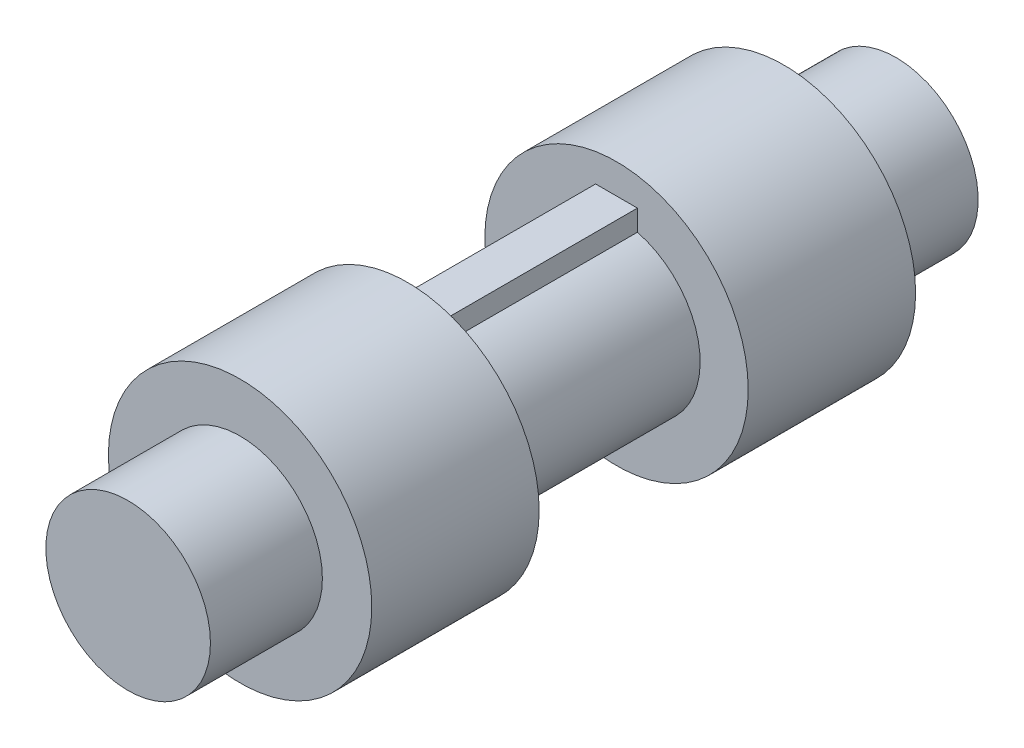
SolidWorks part; units mm, degrees
ref_plane "Front Plane" through (0, 0, 0) normal (0, 0, 1) x (1, 0, 0)
ref_plane "Top Plane" through (0, 0, 0) normal (0, 1, 0) x (1, 0, 0)
ref_plane "Right Plane" through (0, 0, 0) normal (1, 0, 0) x (0, 0, -1)
sketch "Sketch1" plane through (0, 0, 0) normal (0, 0, 1) x (1, 0, 0)
  circle A0 centre (0, 0) radius 12.5
  dimension "D1" = 25
extrude "Boss-Extrude1" add sketch "Sketch1" against normal blind 17
sketch "Sketch2" plane through (0, 0, -17) normal (0, 0, -1) x (-1, 0, 0)
  circle A0 centre (0, 0) radius 20
  dimension "D1" = 40
extrude "Boss-Extrude2" add sketch "Sketch2" along normal blind 25.425
sketch "Sketch3" plane through (0, 0, -42.425) normal (0, 0, -1) x (-1, 0, 0)
  circle A0 centre (0, 0) radius 12.7
  dimension "D1" = 25.4
extrude "Boss-Extrude3" add sketch "Sketch3" along normal blind 31.75
sketch "Sketch6" plane through (0, 0, -74.175) normal (0, 0, -1) x (-1, 0, 0)
  line L0 (0, 0) -> (0, 39.1091) construction
  line L2 (3.175, 15.4717) -> (-3.175, 15.4717)
  line L3 (3.175, 15.4717) -> (3.175, 12.2967)
  line L4 (3.175, 12.2967) -> (-3.175, 12.2967)
  line L5 (-3.175, 15.4717) -> (-3.175, 12.2967)
  line L6 (3.175, 15.4717) -> (-3.175, 12.2967) construction
  line L7 (3.175, 12.2967) -> (-3.175, 15.4717) construction
  circle A0 centre (0, 0) radius 12.7 construction
  point P3 (0, 13.8842)
  dimension "D1" = 6.35
  dimension "D2" = 3.175
extrude "Boss-Extrude6" add sketch "Sketch6" against normal up to surface (31.75 mm away) up to face at (-12.7, 0, -42.425)
sketch "Sketch4" plane through (0, 0, -74.175) normal (0, 0, -1) x (-1, 0, 0)
  circle A0 centre (0, 0) radius 20
  dimension "D1" = 40
extrude "Boss-Extrude4" add sketch "Sketch4" along normal blind 25.425
sketch "Sketch5" plane through (0, 0, -99.6) normal (0, 0, -1) x (-1, 0, 0)
  circle A0 centre (0, 0) radius 12.5
  dimension "D1" = 25
extrude "Boss-Extrude5" add sketch "Sketch5" along normal blind 17
